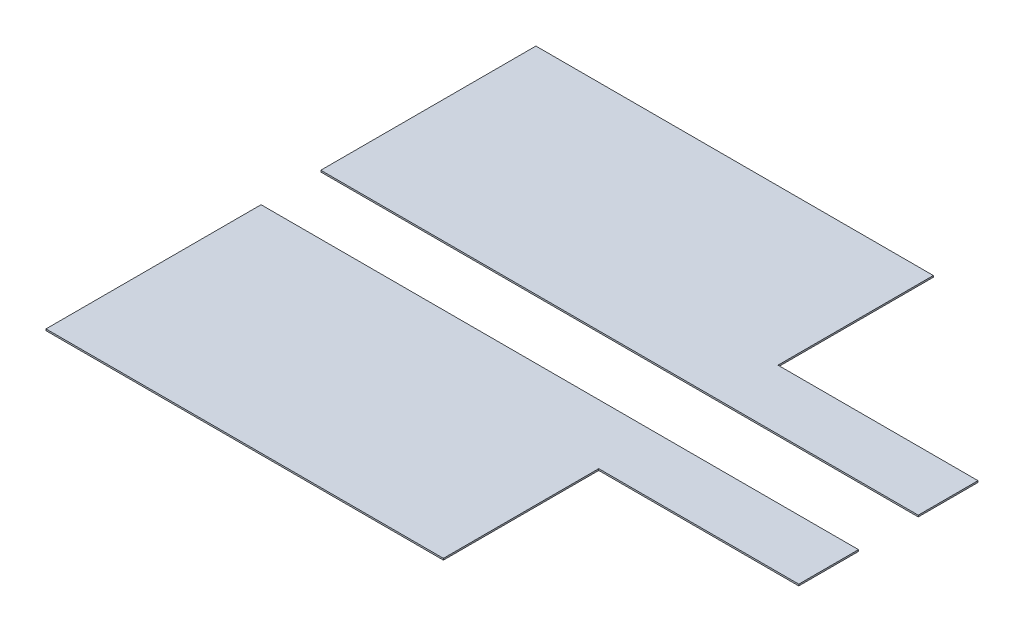
SolidWorks part; units mm, degrees
ref_plane "Front Plane" through (0, 0, 0) normal (0, 0, 1) x (1, 0, 0)
ref_plane "Top Plane" through (0, 0, 0) normal (0, 1, 0) x (1, 0, 0)
ref_plane "Right Plane" through (0, 0, 0) normal (1, 0, 0) x (0, 0, -1)
sketch "Sketch1" plane through (0, 0, 0) normal (0, 1, 0) x (1, 0, 0)
  line L19 (0, 1.25) -> (25, 1.25)
  line L20 (25, 1.25) -> (25, 3.75)
  line L21 (25, 3.75) -> (16.63, 3.75)
  line L22 (16.63, 3.75) -> (16.63, 10.25)
  line L23 (16.63, 10.25) -> (0, 10.25)
  line L24 (0, 10.25) -> (0, 1.25)
  line L32 (0, -1.25) -> (25, -1.25)
  line L33 (25, -1.25) -> (25, -3.75)
  line L34 (25, -3.75) -> (16.63, -3.75)
  line L35 (16.63, -3.75) -> (16.63, -10.25)
  line L36 (16.63, -10.25) -> (0, -10.25)
  line L37 (0, -10.25) -> (0, -1.25)
  dimension "D1" = 2.5
  dimension "D2" = 25
  dimension "D3" = 9
  dimension "D4" = 2.5
  dimension "D5" = 16.63
  dimension "D6" = 9
  dimension "D7" = 16.63
  dimension "D8" = 2.5
extrude "Boss-Extrude1" add sketch "Sketch1" along normal blind 0.0666
